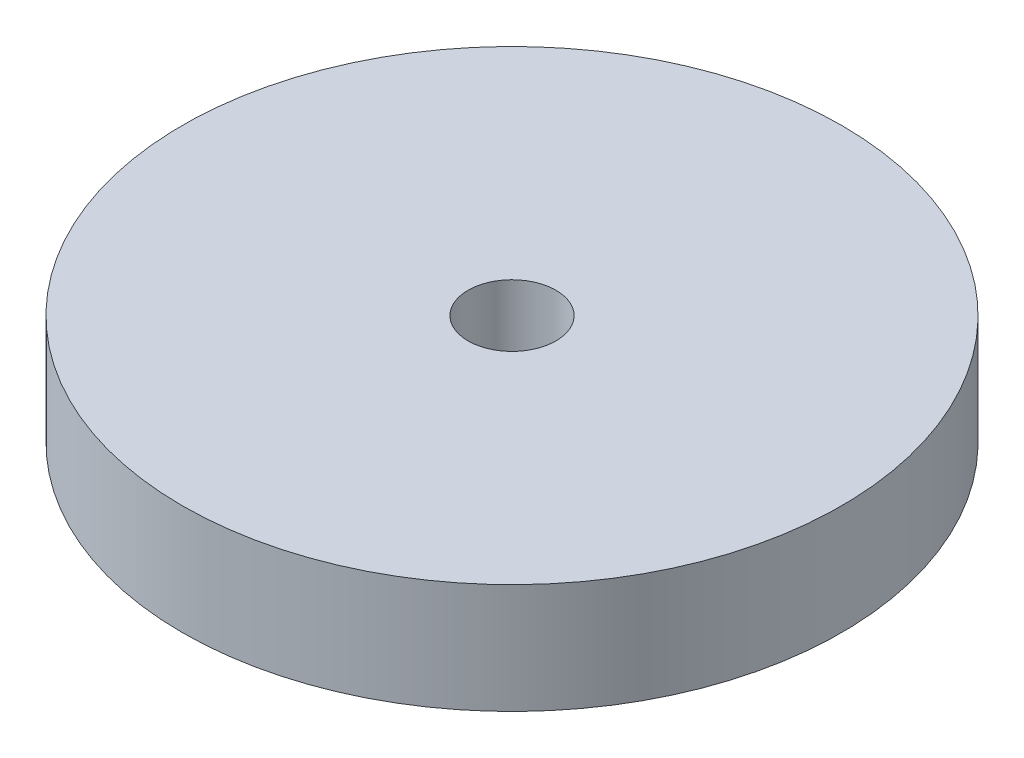
SolidWorks part; units mm, degrees
ref_plane "Front Plane" through (0, 0, 0) normal (0, 0, 1) x (1, 0, 0)
ref_plane "Top Plane" through (0, 0, 0) normal (0, 1, 0) x (1, 0, 0)
ref_plane "Right Plane" through (0, 0, 0) normal (1, 0, 0) x (0, 0, -1)
sketch "Sketch1" plane through (0, 0, 0) normal (0, 1, 0) x (1, 0, 0)
  circle A0 centre (0, 0) radius 4
  circle A1 centre (0, 0) radius 30
  dimension "D1" = 8
  dimension "D2" = 60
extrude "Boss-Extrude1" add sketch "Sketch1" along normal blind 10
